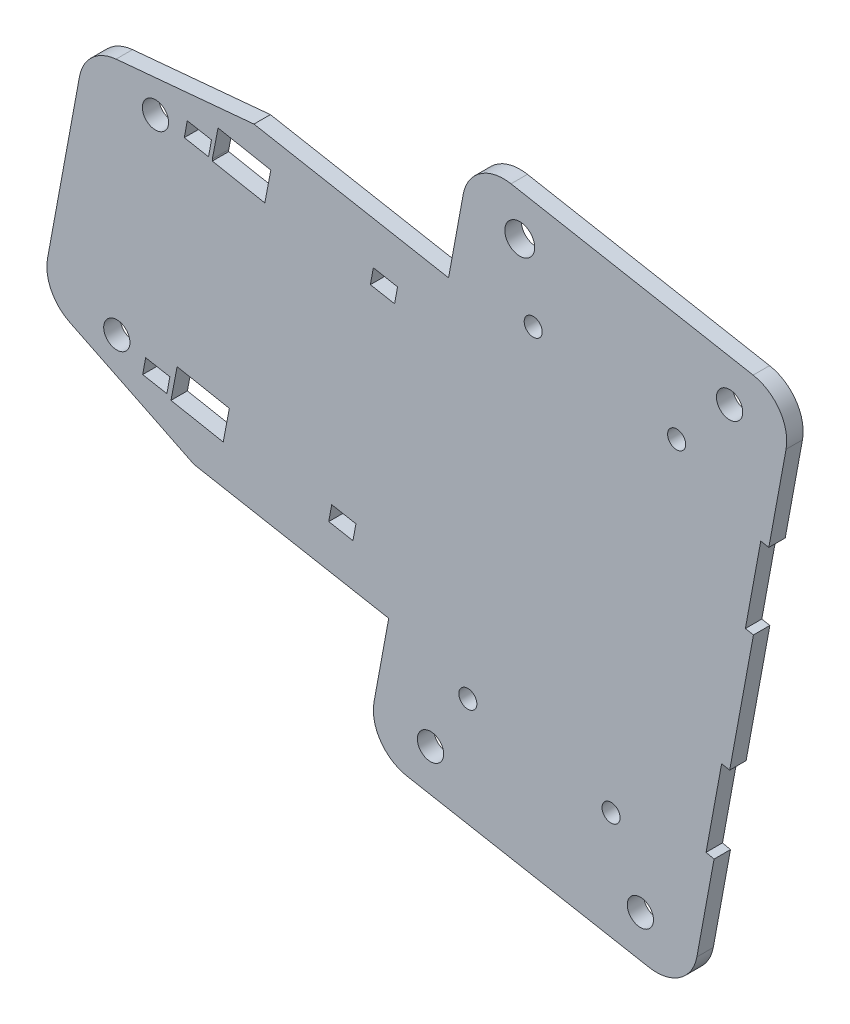
SolidWorks part; units mm, degrees
ref_plane "Front Plane" through (0, 0, 0) normal (0, 0, 1) x (1, 0, 0)
ref_plane "Top Plane" through (0, 0, 0) normal (0, 1, 0) x (1, 0, 0)
ref_plane "Right Plane" through (0, 0, 0) normal (1, 0, 0) x (0, 0, -1)
sketch "Sketch1" plane through (0, 0, 0) normal (0, 0, 1) x (1, 0, 0)
  line L0 (-1.0611, 5.2796) -> (28.4425, -0.1554)
  line L1 (32.4539, -5.9785) -> (21.584, -64.9856)
  line L2 (15.7609, -68.9971) -> (-13.7427, -63.5621)
  line L3 (-17.7541, -57.739) -> (-15.9642, -48.0228)
  line L4 (-5.9783, 6.1854) -> (-18.6599, -62.6563) construction
  line L5 (-15.9642, -48.0228) -> (-39.6736, -43.6552)
  line L6 (-39.6736, -43.6552) -> (-52.9396, -37.1504)
  line L8 (-12.3191, -28.2354) -> (-71.3263, -17.3655) construction
  line L9 (-12.3191, -28.2354) -> (27.019, -35.482) construction
  line L10 (-6.8842, 1.2682) -> (-8.674, -8.4481)
  line L11 (-32.3834, -4.0805) -> (-47.0965, -5.4311)
  line L12 (-8.674, -8.4481) -> (-32.3834, -4.0805)
  line L17 (-52.9396, -37.1504) -> (-54.8219, -36.2275)
  line L18 (-52.3301, -2.562) -> (-58.852, -37.9663) construction
  line L19 (-57.5378, -30.8323) -> (-53.6443, -9.696)
  line L20 (-47.0965, -5.4311) -> (-49.1841, -5.6228)
  line L21 (-12.3191, -28.2354) -> (-55.591, -20.2641) construction
  line L30 (-42.4966, -38.2911) -> (-41.7468, -34.3624)
  line L31 (-41.7468, -34.3624) -> (-35.3804, -35.5774)
  line L32 (-35.3804, -35.5774) -> (-36.1302, -39.5061)
  line L33 (-36.1302, -39.5061) -> (-42.4966, -38.2911)
  line L35 (-37.4583, -10.3138) -> (-36.7637, -6.6745)
  line L36 (-36.7637, -6.6745) -> (-30.3297, -7.9024)
  line L37 (-30.3297, -7.9024) -> (-31.0627, -11.7434)
  line L38 (-31.0627, -11.7434) -> (-37.4583, -10.5228)
  line L39 (-37.4583, -10.5228) -> (-37.4583, -10.3138)
  arc A4 (-13.7427, -63.5621) -> (-17.7541, -57.739) centre (-12.8368, -58.6448) cw
  arc A5 (-1.0611, 5.2796) -> (-6.8842, 1.2682) centre (-1.9669, 0.3623) ccw
  arc A6 (28.4425, -0.1554) -> (32.4539, -5.9785) centre (27.5367, -5.0726) cw
  arc A7 (21.584, -64.9856) -> (15.7609, -68.9971) centre (16.6668, -64.0798) cw
  circle A8 centre (-44.3848, -9.1098) radius 1.6
  circle A9 centre (-49.0951, -34.6795) radius 1.6
  circle A10 centre (-10.8699, -59.0072) radius 1.6
  circle A11 centre (14.6998, -63.7175) radius 1.6
  circle A12 centre (0, 0) radius 1.8216
  circle A13 centre (25.5698, -4.7103) radius 1.6
  arc A14 (-54.8219, -36.2275) -> (-57.5378, -30.8323) centre (-52.6206, -31.7381) cw
  arc A15 (-49.1841, -5.6228) -> (-53.6443, -9.696) centre (-48.727, -10.6019) ccw
  point P23 (-53.6061, -20.6298)
  point P29 (-58.2244, -34.5591)
  point P32 (-18.6599, -62.6563)
  point P35 (-5.9783, 6.1854)
  point P38 (33.3598, -1.0612)
  point P41 (20.6782, -69.9029)
  point P63 (-55.591, -20.2641)
  dimension "D1" = 5
  dimension "D2" = 5
extrude "Boss-Extrude1" add sketch "Sketch1" along normal blind 2
sketch "Sketch2" plane through (0, 0, 2) normal (0, 0, 1) x (1, 0, 0)
  line L0 (-12.3191, -28.2354) -> (-71.3263, -17.3655) construction
  line L5 (-42.6315, -35.8702) -> (-45.5819, -35.3267)
  line L6 (-45.5819, -35.3267) -> (-45.9442, -37.2936)
  line L7 (-45.9442, -37.2936) -> (-42.9939, -37.8371)
  line L8 (-42.9939, -37.8371) -> (-42.6315, -35.8702)
  line L9 (-40.5093, -7.79) -> (-37.5589, -8.3335)
  line L10 (-40.8716, -9.7569) -> (-40.5093, -7.79)
  line L11 (-37.9212, -10.3004) -> (-40.8716, -9.7569)
  line L12 (-37.5589, -8.3335) -> (-37.9212, -10.3004)
  line L13 (-22.9086, -39.5034) -> (-19.9583, -40.0469)
  line L14 (-22.9086, -39.5034) -> (-23.271, -41.4703)
  line L15 (-23.271, -41.4703) -> (-20.3206, -42.0138)
  line L16 (-20.3206, -42.0138) -> (-19.9583, -40.0469)
  line L17 (-17.836, -11.9668) -> (-14.8856, -12.5102)
  line L18 (-18.1983, -13.9337) -> (-17.836, -11.9668)
  line L19 (-18.1983, -13.9337) -> (-15.248, -14.4772)
  line L20 (-14.8856, -12.5102) -> (-15.248, -14.4772)
  dimension "D1" = 13
  dimension "D2" = 13
  dimension "D3" = 3
  dimension "D4" = 2
  dimension "D5" = 13
  dimension "D6" = 13
  dimension "D7" = 2
  dimension "D8" = 3
extrude "Cut-Extrude1" cut sketch "Sketch2" against normal blind 2
sketch "Sketch3" plane through (0, 0, 2) normal (0, 0, 1) x (1, 0, 0)
  line L0 (-12.3191, -28.2354) -> (27.019, -35.482) construction
  line L1 (-5.9783, 6.1854) -> (-18.6599, -62.6563) construction
  line L2 (21.584, -64.9856) -> (32.4539, -5.9785) construction
  line L3 (22.7044, -53.3879) -> (24.6009, -43.0886)
  line L5 (24.6009, -43.0886) -> (25.5844, -43.2698)
  line L6 (25.5844, -43.2698) -> (23.6802, -53.6065)
  line L7 (23.6802, -53.6065) -> (22.7044, -53.3879)
  line L8 (28.4792, -27.5552) -> (27.4958, -27.3741)
  line L9 (27.4958, -27.3741) -> (29.3688, -17.206)
  line L10 (29.3688, -17.206) -> (30.3523, -17.3872)
  line L11 (30.3523, -17.3872) -> (28.4792, -27.5552)
  circle A0 centre (-6.3228, -51.6963) radius 1.1
  circle A1 centre (11.1269, -54.9863) radius 1.1
  circle A2 centre (19.1202, -11.5951) radius 1.1
  circle A3 centre (1.6435, -8.4512) radius 1.1
  dimension "D1" = 2.2
  dimension "D2" = 2.2
  dimension "D3" = 1
  dimension "D4" = 1
  dimension "D5" = 10.4724
  dimension "1" = 1
  dimension "D6" = 1
extrude "Cut-Extrude2" cut sketch "Sketch3" against normal up to next
